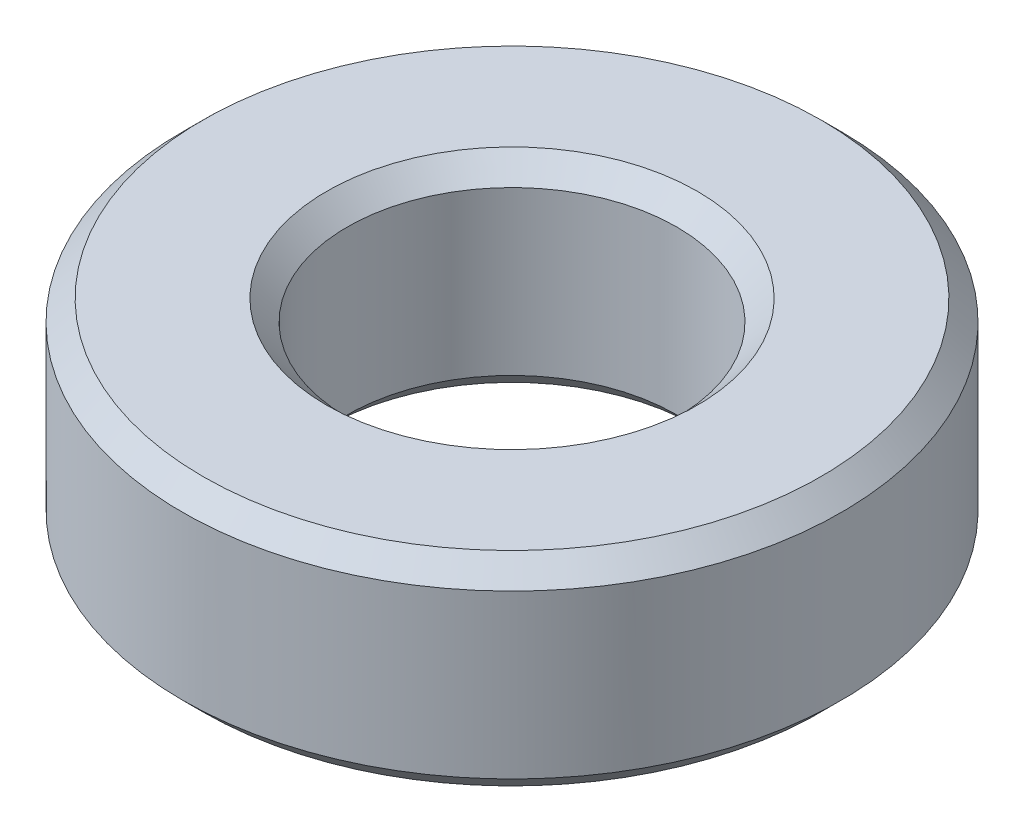
SolidWorks part; units mm, degrees
ref_plane "Front Plane" through (0, 0, 0) normal (0, 0, 1) x (1, 0, 0)
ref_plane "Top Plane" through (0, 0, 0) normal (0, 1, 0) x (1, 0, 0)
ref_plane "Right Plane" through (0, 0, 0) normal (1, 0, 0) x (0, 0, -1)
sketch "Sketch1" plane through (0, 0, 0) normal (0, 1, 0) x (1, 0, 0)
  circle A0 centre (0, 0) radius 4
  circle A1 centre (0, 0) radius 8
  dimension "D1" = 16
  dimension "D2" = 8
extrude "Boss-Extrude1" add sketch "Sketch1" along normal blind 4.95
chamfer "Chamfer1" distance 0.5 angle 45 4 edges at (0, 0, 4) (0, 0, 8) (0, 4.95, 4) (0, 4.95, 8)
